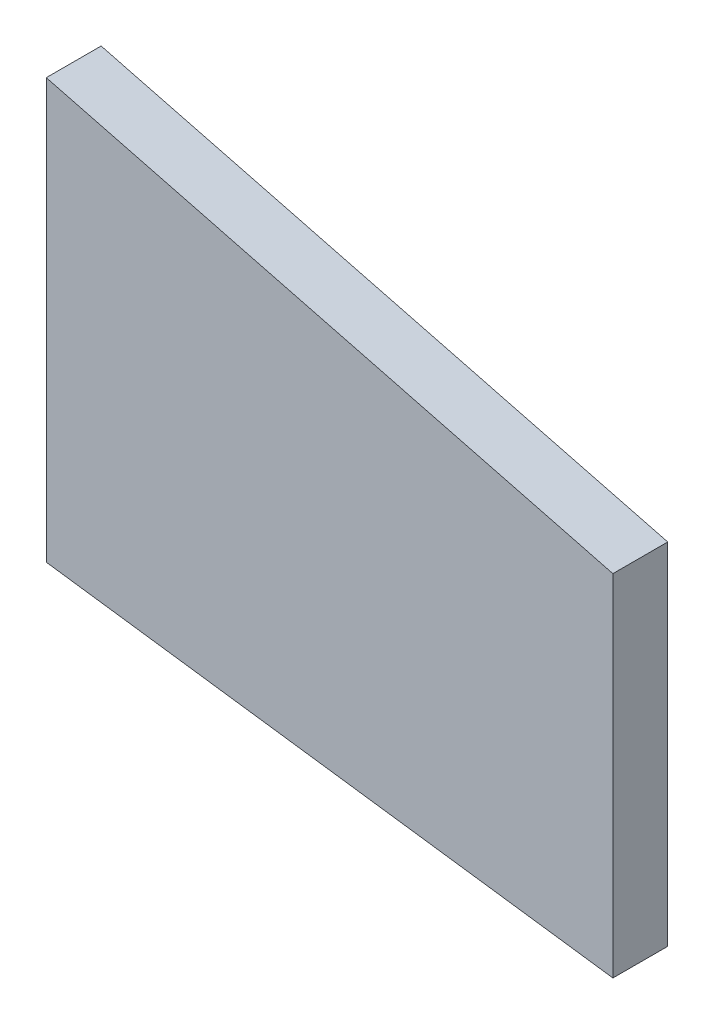
SolidWorks part; units mm, degrees
ref_plane "Front Plane" through (0, 0, 0) normal (0, 0, 1) x (1, 0, 0)
ref_plane "Top Plane" through (0, 0, 0) normal (0, 1, 0) x (1, 0, 0)
ref_plane "Right Plane" through (0, 0, 0) normal (1, 0, 0) x (0, 0, -1)
sketch "Sketch1" plane through (0, 0, 0) normal (0, 0, 1) x (1, 0, 0)
  line L0 (0, 0) -> (196.85, 0)
  line L1 (196.85, 0) -> (196.85, 127)
  line L2 (0, 0) -> (0, 177.8)
  line L3 (0, 177.8) -> (196.85, 127)
  dimension "D1" = 177.8
  dimension "D2" = 196.85
  dimension "D3" = 127
  dimension "D4" = 104.47
extrude "Boss-Extrude1" add sketch "Sketch1" along normal blind 19.05
sketch "Sketch3" plane through (0, 0, 19.05) normal (0, 0, 1) x (1, 0, 0)
  line L0 (0, 0) -> (0, 32.004)
  line L1 (0, 177.8) -> (0, 0) construction
  line L2 (0, 32.004) -> (196.85, 5.334)
  line L3 (196.85, 0) -> (196.85, 127) construction
  line L4 (196.85, 5.334) -> (196.85, 0)
  line L5 (196.85, 0) -> (0, 0)
  point P5 (0, 41.1662)
  point P11 (196.85, 13.4634)
  dimension "D1" = 32.004
  dimension "D2" = 5.334
extrude "Cut-Extrude2" cut sketch "Sketch3" against normal blind 781.6864
